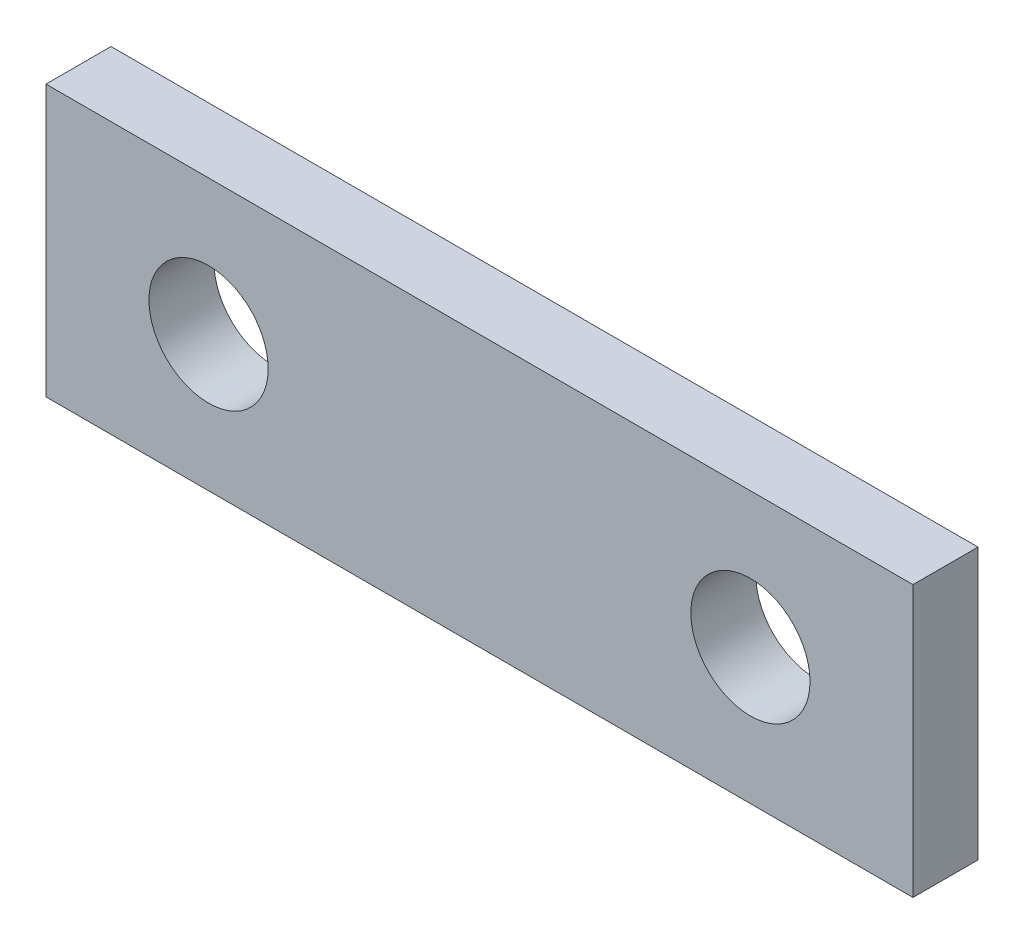
SolidWorks part; units mm, degrees
material "1.0037 (S235JR)"
ref_plane "E_Rechts" through (0, 0, 0) normal (0, 0, 1) x (1, 0, 0)
ref_plane "E_Vorne" through (0, 0, 0) normal (0, 1, 0) x (1, 0, 0)
ref_plane "E_Oben" through (0, 0, 0) normal (1, 0, 0) x (0, 0, -1)
sketch "Skizze1" plane through (0, 0, 0) normal (0, 0, 1) x (1, 0, 0)
  line L0 (55, 0) -> (-55, 0) construction
  line L1 (-40, 12.5) -> (40, 12.5)
  line L2 (-40, 12.5) -> (-40, -12.5)
  line L3 (-40, -12.5) -> (40, -12.5)
  line L4 (40, 12.5) -> (40, -12.5)
  line L5 (0, -55) -> (0, 55) construction
  circle A0 centre (-25, 0) radius 5.5
  circle A1 centre (25, 0) radius 5.5
  dimension "D7" = 11
  dimension "D8" = 11
  dimension "D1" = 80
  dimension "D2" = 25
  dimension "D3" = 12.5
  dimension "D4" = 40
  dimension "D5" = 50
  dimension "D6" = 25
extrude "Aufsatz-Linear austragen1" add sketch "Skizze1" along normal mid plane 6
